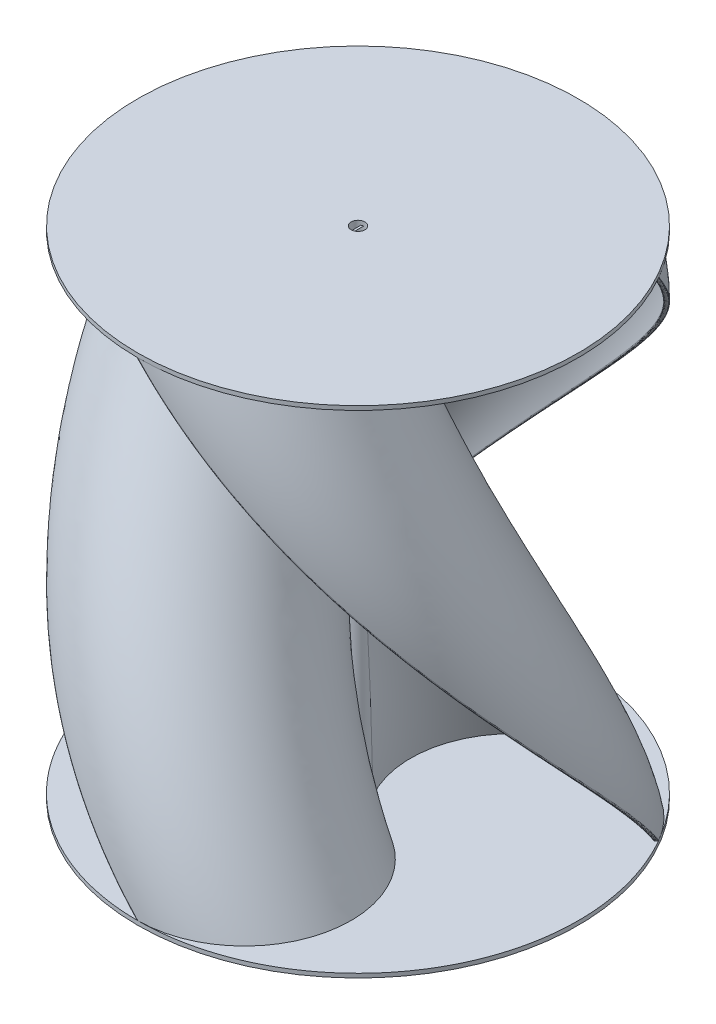
SolidWorks part; units mm, degrees
ref_plane "Front Plane" through (0, 0, 0) normal (0, 0, 1) x (1, 0, 0)
ref_plane "Top Plane" through (0, 0, 0) normal (0, 1, 0) x (1, 0, 0)
ref_plane "Right Plane" through (0, 0, 0) normal (1, 0, 0) x (0, 0, -1)
sketch "Sketch1" plane through (0, 0, 0) normal (0, 1, 0) x (1, 0, 0)
  circle A0 centre (0, 0) radius 160
  dimension "D1" = 320
curve "Helix/Spiral1" pitch 1062 height 354 turns 0.3333
ref_axis "Axis1" through (0, 371.7, 0) along (0, -1, 0)
sketch "Sketch2" plane through (0, 0, 0) normal (0, 1, 0) x (1, 0, 0)
  circle A0 centre (0, 0) radius 8
  circle A1 centre (0, 0) radius 5
  dimension "D1" = 16
  dimension "D2" = 10
extrude "Boss-Extrude1" add sketch "Sketch2" along normal blind 354
sketch "Sketch3" plane through (0, 0, 0) normal (0, 1, 0) x (1, 0, 0)
  line L0 (0, 0) -> (0, -190.9876) construction
  arc A0 (0, -6.5) -> (0, -158.5) centre (0, -82.5) cw construction
  arc A1 (0, -160) -> (0, -5) centre (0, -82.5) ccw
  arc A2 (0, -157) -> (0, -8) centre (0, -82.5) ccw
  arc A3 (0, -157) -> (0, -160) centre (0, -158.5) ccw
  arc A4 (0, -5) -> (0, -8) centre (0, -6.5) ccw
  circle A5 centre (0, 0) radius 160 construction
  circle A6 centre (0, 0) radius 5 construction
  point P7 (76, -82.5)
  dimension "D1" = 3
sweep "Sweep1" add profiles "Sketch3" path "Helix/Spiral1"
pattern_circular "CirPattern1" count 3 over 360 about axis through (0, 371.7, 0) along (0, -1, 0) of "Sweep1"
sketch "Sketch4" plane through (0, 354, 0) normal (0, 1, 0) x (1, 0, 0)
  circle A0 centre (0, 0) radius 160
  arc A1 (135.9657, 78.5005) -> (138.5638, 80.0004) centre (137.2647, 79.2505) ccw construction
  circle A2 centre (0, 0) radius 5 construction
  circle A3 centre (0, 0) radius 5
extrude "Boss-Extrude2" add sketch "Sketch4" along normal blind 3
sketch "Sketch5" plane through (0, 0, 0) normal (0, -1, 0) x (1, 0, 0)
  circle A0 centre (0, 0) radius 160
  arc A1 (-138.5641, -80) -> (-135.966, -78.5) centre (-137.265, -79.25) ccw construction
  circle A2 centre (0, 0) radius 5 construction
  circle A3 centre (0, 0) radius 5
extrude "Boss-Extrude3" add sketch "Sketch5" along normal blind 3
